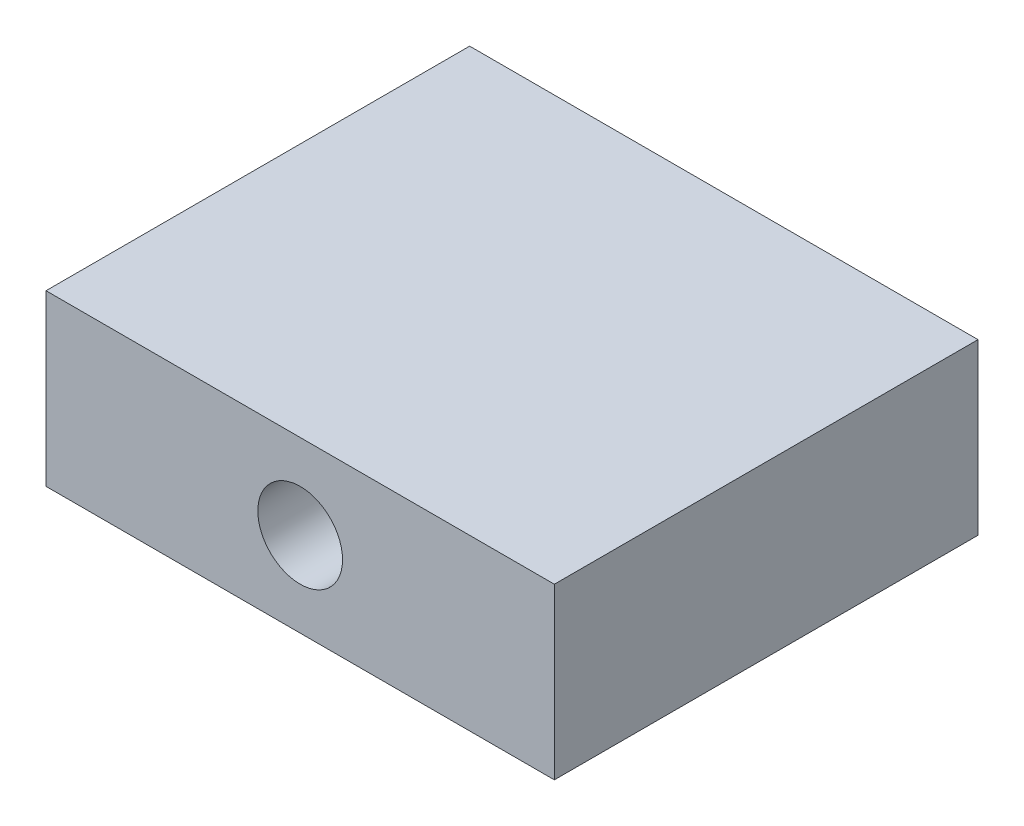
SolidWorks part; units mm, degrees
material "ABS"
ref_plane "前基準面" through (0, 0, 0) normal (0, 0, 1) x (1, 0, 0)
ref_plane "上基準面" through (0, 0, 0) normal (0, 1, 0) x (1, 0, 0)
ref_plane "右基準面" through (0, 0, 0) normal (1, 0, 0) x (0, 0, -1)
sketch "草圖1" plane through (0, 0, 0) normal (0, 0, 1) x (1, 0, 0)
  line L0 (0, 0) -> (60, 20) construction
  line L1 (0, 0) -> (60, 0)
  line L2 (0, 0) -> (0, 20)
  line L3 (0, 20) -> (60, 20)
  line L4 (60, 0) -> (60, 20)
  circle A0 centre (30, 10) radius 5
  dimension "D1" = 10
  dimension "D2" = 60
  dimension "D3" = 20
extrude "填料-伸長1" add sketch "草圖1" along normal mid plane 50
